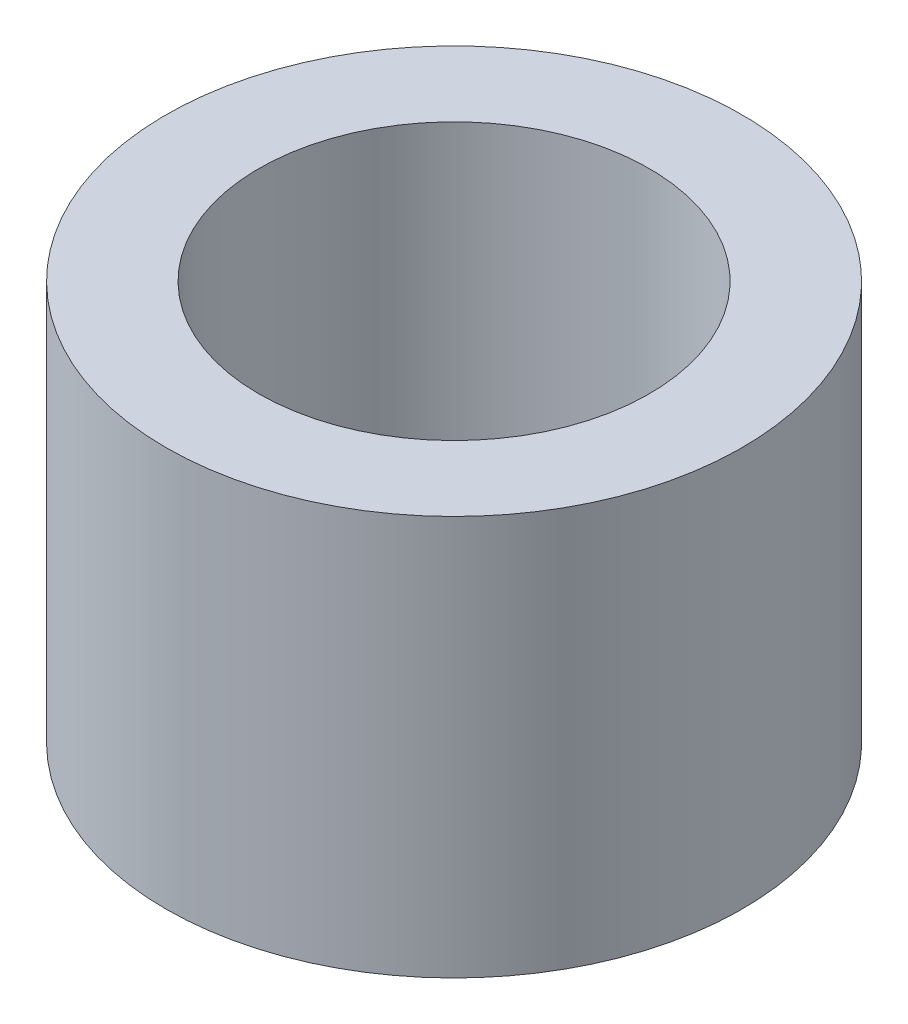
SolidWorks part; units mm, degrees
ref_plane "Front Plane" through (0, 0, 0) normal (0, 0, 1) x (1, 0, 0)
ref_plane "Top Plane" through (0, 0, 0) normal (0, 1, 0) x (1, 0, 0)
ref_plane "Right Plane" through (0, 0, 0) normal (1, 0, 0) x (0, 0, -1)
sketch "Sketch1" plane through (0, 0, 0) normal (0, 1, 0) x (1, 0, 0)
  circle A0 centre (0, 0) radius 2.667
  circle A1 centre (0, 0) radius 3.937
  dimension "D1" = 5.334
  dimension "D2" = 7.874
extrude "Boss-Extrude1" add sketch "Sketch1" along normal blind 5.461
